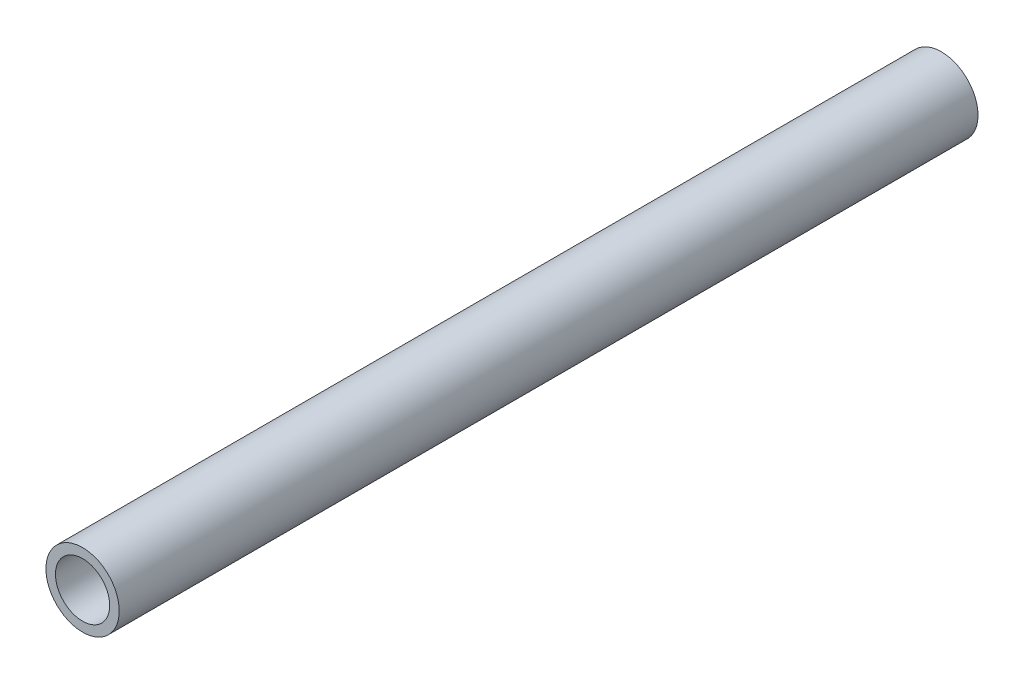
SolidWorks part; units mm, degrees
ref_plane "Front Plane" through (0, 0, 0) normal (0, 0, 1) x (1, 0, 0)
ref_plane "Top Plane" through (0, 0, 0) normal (0, 1, 0) x (1, 0, 0)
ref_plane "Right Plane" through (0, 0, 0) normal (1, 0, 0) x (0, 0, -1)
sketch "Sketch1" plane through (0, 0, 0) normal (0, 0, 1) x (1, 0, 0)
  circle A0 centre (0, 0) radius 10.668
  dimension "Pipe OD" = 21.336
extrude "Extrude-Thin1" add sketch "Sketch1" along normal mid plane 250 thin thin type one direction reverse wall 2.7686
